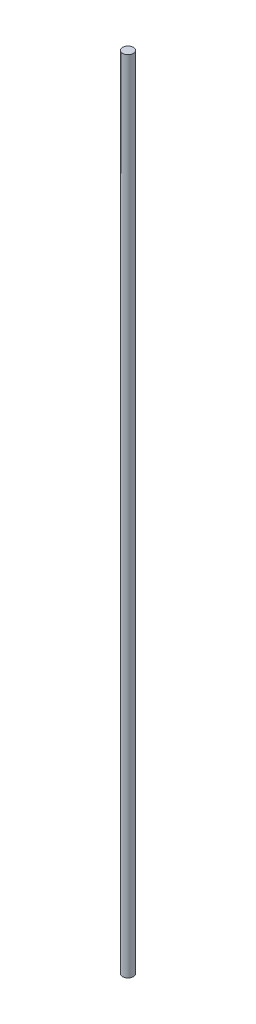
SolidWorks part; units mm, degrees
material "AISI Тип 316L нержавеющая сталь"
ref_plane "Front" through (0, 0, 0) normal (0, 0, 1) x (1, 0, 0)
ref_plane "Top" through (0, 0, 0) normal (0, 1, 0) x (1, 0, 0)
ref_plane "Right" through (0, 0, 0) normal (1, 0, 0) x (0, 0, -1)
sketch "Sketch1" plane through (0, 0, 0) normal (0, 1, 0) x (1, 0, 0)
  circle A0 centre (0, 0) radius 4
  dimension "D1" = 8
extrude "Boss-Extrude1" add sketch "Sketch1" along normal blind 600
